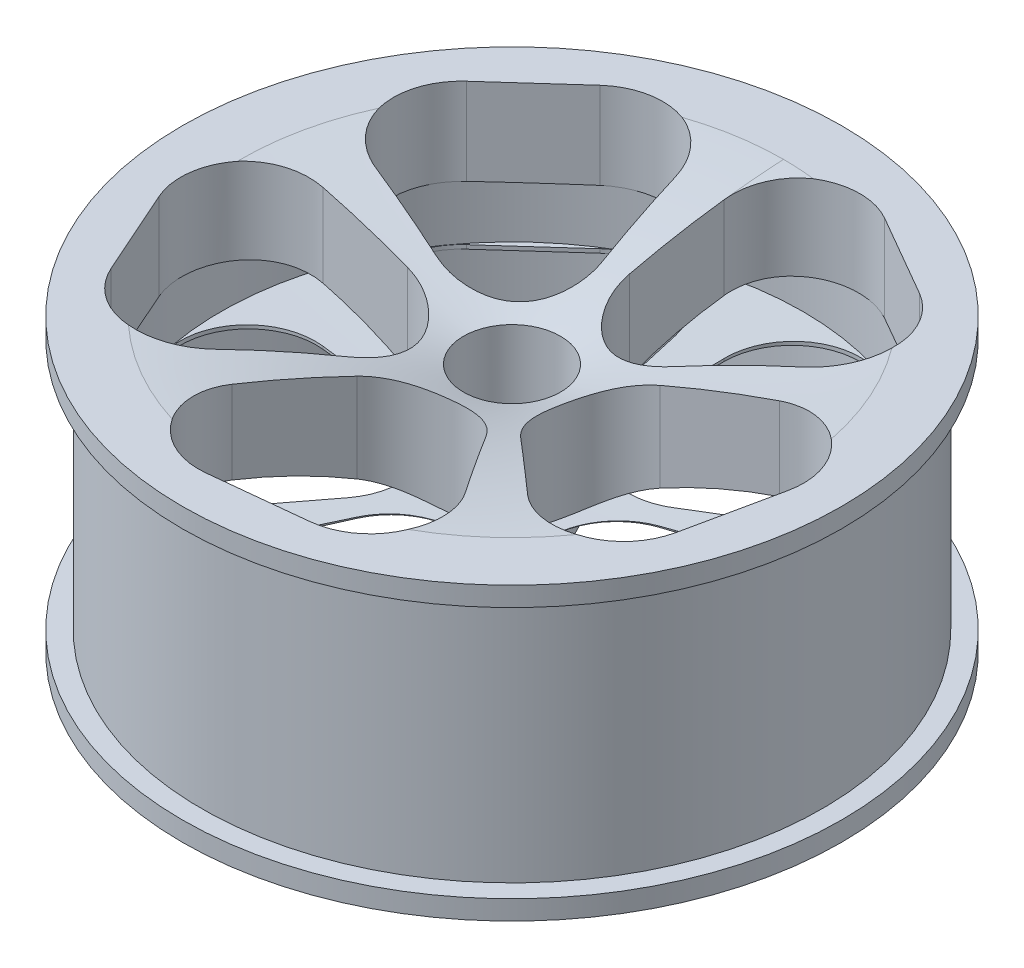
SolidWorks part; units mm, degrees
ref_plane "Front Plane" through (0, 0, 0) normal (0, 0, 1) x (1, 0, 0)
ref_plane "Top Plane" through (0, 0, 0) normal (0, 1, 0) x (1, 0, 0)
ref_plane "Right Plane" through (0, 0, 0) normal (1, 0, 0) x (0, 0, -1)
sketch "Sketch1" plane through (0, 0, 0) normal (0, 1, 0) x (1, 0, 0)
  circle A0 centre (0, 0) radius 50
  dimension "D1" = 100
extrude "Boss-Extrude1" add sketch "Sketch1" along normal blind 30
sketch "Sketch2" plane through (0, 0, 0) normal (0, 0, 1) x (1, 0, 0)
  line L0 (0, 0) -> (0, 43.8673) construction
  line L1 (-300, -27.7209) -> (-300, 180)
  line L2 (-300, 180) -> (-340, 180)
  line L3 (-340, 180) -> (-340, 160)
  line L4 (-340, 160) -> (-320, 160)
  line L5 (-320, 160) -> (-320, -100)
  line L6 (-320, -100) -> (-340, -100)
  line L7 (-340, -100) -> (-340, -120)
  line L8 (-340, -120) -> (-300, -120)
  line L9 (-300, -120) -> (-300, -27.7209)
  line L10 (50, 30) -> (-50, 30) construction
  dimension "D1" = 20
  dimension "D2" = 300
  dimension "D3" = 20
  dimension "D4" = 40
  dimension "D5" = 300
  dimension "D6" = 150
revolve "Revolve2" add sketch "Sketch2" angle 360 about L0
sketch "Sketch3" plane through (0, 30, 0) normal (0, 1, 0) x (1, 0, 0)
  line L0 (105, 60.6218) -> (189.4486, 109.3782)
  line L1 (189.4486, 230.6218) -> (105, 279.3782)
  line L2 (0, 218.7564) -> (0, 121.2436)
  line L3 (208.0497, 67.5995) -> (115.3095, 37.4663)
  line L4 (90.1015, -81.1278) -> (162.5677, -146.3766)
  line L5 (277.8772, -108.9103) -> (298.1513, -13.5283)
  line L6 (128.5818, -176.9777) -> (71.2652, -98.0881)
  line L7 (-49.3142, -110.7615) -> (-88.9763, -199.844)
  line L8 (-17.7111, -297.9321) -> (79.2676, -287.7392)
  line L9 (-128.5818, -176.9777) -> (-71.2652, -98.0881)
  line L10 (-120.5794, 12.6734) -> (-217.5581, 22.8663)
  line L11 (-288.8232, -75.2218) -> (-249.1612, -164.3043)
  line L12 (-208.0497, 67.5995) -> (-115.3095, 37.4663)
  line L13 (-25.208, 118.5941) -> (-45.482, 213.9761)
  line L14 (-160.7915, 251.4424) -> (-233.2577, 186.1936)
  arc A0 (105, 279.3782) -> (0, 218.7564) centre (70, 218.7564) ccw
  circle A1 centre (0, 0) radius 50
  circle A2 centre (0, 0) radius 50
  circle A3 centre (0, 0) radius 340
  circle A4 centre (0, 0) radius 340
  arc A5 (189.4486, 230.6218) -> (189.4486, 109.3782) centre (154.4486, 170) cw
  arc A6 (105, 60.6218) -> (0, 121.2436) centre (70, 121.2436) cw
  arc A7 (90.1015, -81.1278) -> (115.3095, 37.4663) centre (136.9407, -29.1076) cw
  arc A8 (298.1513, -13.5283) -> (208.0497, 67.5995) centre (229.6809, 1.0255) ccw
  arc A9 (277.8772, -108.9103) -> (162.5677, -146.3766) centre (209.4069, -94.3565) cw
  arc A10 (-49.3142, -110.7615) -> (71.2652, -98.0881) centre (14.634, -139.2331) cw
  arc A11 (79.2676, -287.7392) -> (128.5818, -176.9777) centre (71.9506, -218.1226) ccw
  arc A12 (-17.7111, -297.9321) -> (-88.9763, -199.844) centre (-25.0281, -228.3155) cw
  arc A13 (-120.5794, 12.6734) -> (-71.2652, -98.0881) centre (-127.8964, -56.9431) cw
  arc A14 (-249.1612, -164.3043) -> (-128.5818, -176.9777) centre (-185.213, -135.8327) ccw
  arc A15 (-288.8232, -75.2218) -> (-217.5581, 22.8663) centre (-224.8751, -46.7503) cw
  arc A16 (-25.208, 118.5941) -> (-115.3095, 37.4663) centre (-93.6783, 104.0403) cw
  arc A17 (-233.2577, 186.1936) -> (-208.0497, 67.5995) centre (-186.4186, 134.1734) ccw
  arc A18 (-160.7915, 251.4424) -> (-45.482, 213.9761) centre (-113.9524, 199.4223) cw
  point P10 (0, 340)
  point P13 (294.4486, 170)
  point P55 (0, 0)
  dimension "D4" = 70
  dimension "D3" = 60
  dimension "D1" = 0
  dimension "D2" = 0
  dimension "D5" = 5
extrude "Boss-Extrude2" add sketch "Sketch3" along normal through all
sketch "Sketch4" plane through (0, 0, 0) normal (0, 0, 1) x (1, 0, 0)
  line L0 (0, -60.3082) -> (0, 216.278) construction
  line L1 (-300, 79.2957) -> (-300, 249.0488)
  line L2 (-320, 30) -> (320, 30) construction
  line L3 (-49.8117, 136.9725) -> (0, 136.9725)
  line L5 (0, 173.6758) -> (0, 30)
  line L6 (0, 30) -> (-49.8117, 30)
  line L7 (-300, 216.278) -> (0, 216.278)
  line L8 (0, 216.278) -> (0, 173.6758)
  line L9 (-49.8117, 30) -> (-300, 34.0719)
  line L10 (-300, 34.0719) -> (-300, 83.2282)
  arc A0 (-49.8117, 30) -> (-300, 90.4378) centre (-266.7469, -319.9661) ccw
  arc A1 (-49.8117, 136.9725) -> (-300, 180.8854) centre (-329.7713, -723.3966) ccw
  point P14 (0, 0)
  point P20 (0, 0)
  point P21 (0, 0)
  dimension "D1" = 300
revolve "Cut-Revolve1" cut sketch "Sketch4" angle 360 about L5
sketch "Sketch5" plane through (0, 0, 0) normal (1, 0, 0) x (0, 0, -1)
  line L0 (-320, 30) -> (-320, 160)
  line L1 (-320, 160) -> (-340, 160)
  line L2 (-340, 180) -> (-340, 30) construction
  line L3 (-340, 160) -> (-340, 30)
  line L4 (-340, 30) -> (-320, 30)
  line L5 (340, 180) -> (-340, 180) construction
  line L6 (0, -21.4283) -> (0, 251.785) construction
  dimension "D1" = 20
  dimension "D2" = 20
revolve "Cut-Revolve2" cut sketch "Sketch5" angle 360 about L6
